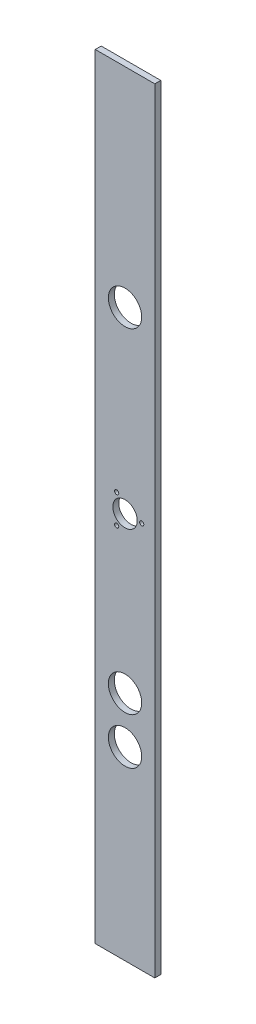
SolidWorks part; units mm, degrees
ref_plane "Plan de face" through (0, 0, 0) normal (0, 0, 1) x (1, 0, 0)
ref_plane "Plan de dessus" through (0, 0, 0) normal (0, 1, 0) x (1, 0, 0)
ref_plane "Plan de droite" through (0, 0, 0) normal (1, 0, 0) x (0, 0, -1)
sketch "Esquisse1" plane through (0, 0, 0) normal (0, 0, 1) x (1, 0, 0)
  line L0 (18, -312.8756) -> (25, -325)
  line L1 (0, 0) -> (50, 0)
  line L2 (0, 0) -> (0, -650)
  line L3 (0, -650) -> (50, -650)
  line L4 (50, 0) -> (50, -650)
  line L5 (25, -325) -> (39, -325)
  line L6 (25, -325) -> (18, -337.1244)
  circle A0 centre (25, -325) radius 10.25
  circle A1 centre (25, -325) radius 14
  circle A2 centre (25, -494.5) radius 14
  circle A3 centre (18, -312.8756) radius 1.75
  circle A4 centre (18, -337.1244) radius 1.75
  circle A5 centre (39, -325) radius 1.75
  circle A6 centre (25, -455.5) radius 14
  circle A7 centre (25, -175) radius 14
  dimension "D5" = 20.5
  dimension "D6" = 120
  dimension "D7" = 28
  dimension "D8" = 3.5
  dimension "D9" = 3.5
  dimension "D10" = 3.5
  dimension "D13" = 28
  dimension "D14" = 28
  dimension "D15" = 28
  dimension "D1" = 50
  dimension "D2" = 650
  dimension "D3" = 25
  dimension "D4" = 325
  dimension "D11" = 120
  dimension "D12" = 90
  dimension "D16" = 25
  dimension "D17" = 25
  dimension "D18" = 130.5
  dimension "D19" = 39
  dimension "D20" = 150
  dimension "D21" = 25
extrude "Boss.-Extru.1" add sketch "Esquisse1" along normal blind 5 contours L4 L1 L2 L3 A5 A1 A4 A3 | A5 A1 A3 L0 A0 L5 | A4 L6 A0 L0 A3 A1 | A5 L5 A0 L6 A4 A1
chamfer "Chanfrein1" distance 1 angle 45 3 edges at (19.75, -337.1244, 0) (19.75, -312.8756, 0) (40.75, -325, 0)
